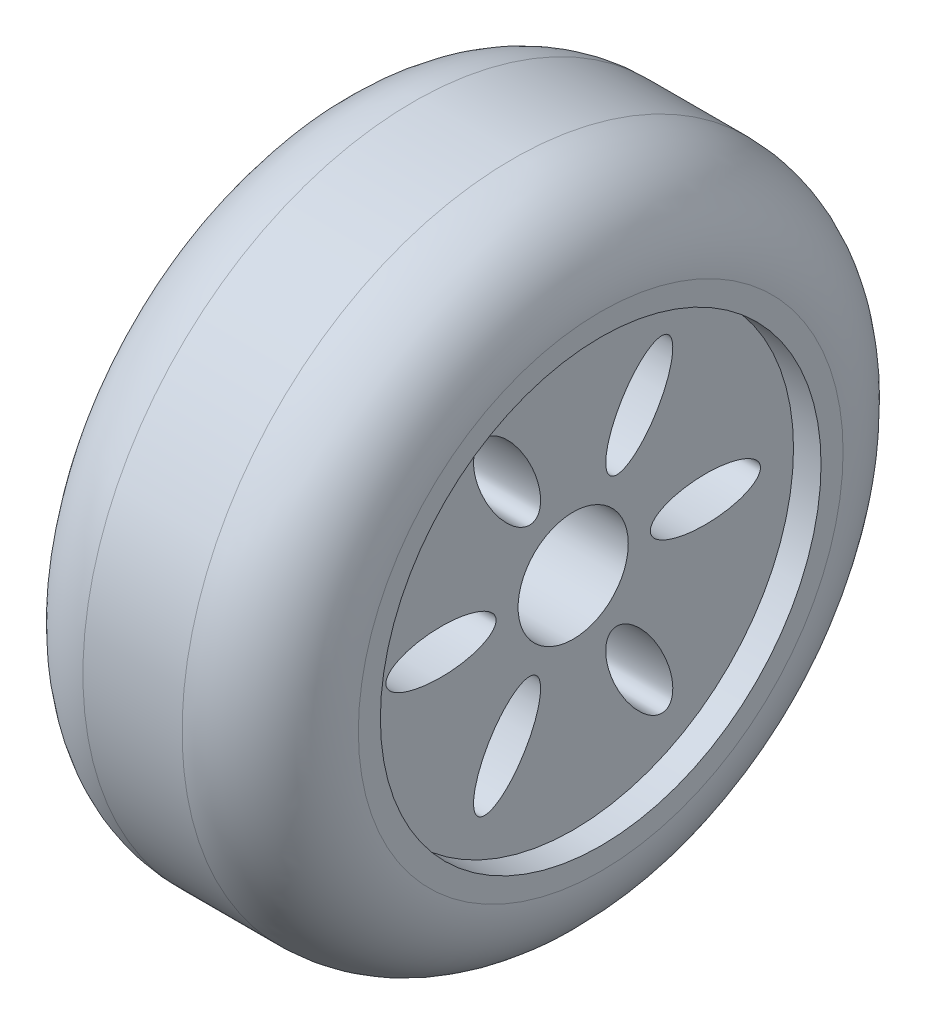
SolidWorks part; units mm, degrees
ref_plane "Front Plane" through (0, 0, 0) normal (0, 0, 1) x (1, 0, 0)
ref_plane "Top Plane" through (0, 0, 0) normal (0, 1, 0) x (1, 0, 0)
ref_plane "Right Plane" through (0, 0, 0) normal (1, 0, 0) x (0, 0, -1)
sketch "Sketch1" plane through (0, 0, 0) normal (1, 0, 0) x (0, 0, -1)
  circle A0 centre (0, 0) radius 30
  circle A1 centre (0, 0) radius 20
  dimension "D1" = 60
  dimension "D2" = 40
extrude "Boss-Extrude1" add sketch "Sketch1" along normal mid plane 25
fillet "Fillet1" radius 8 2 edges at (-12.5, 0, -30) (12.5, 0, -30)
sketch "Sketch2" plane through (0, 0, 0) normal (1, 0, 0) x (0, 0, -1)
  circle A0 centre (0, 0) radius 5
  circle A1 centre (0, 0) radius 20
  circle A17 centre (0, 0) radius 17
  ellipse E0 centre (-12, 0) end of major axis (-17, 0) minor radius 2
  ellipse E1 centre (-6, 10.3923) end of major axis (-8.5, 14.7224) minor radius 2
  ellipse E2 centre (6, 10.3923) end of major axis (8.5, 14.7224) minor radius 2
  ellipse E3 centre (12, 0) end of major axis (17, 0) minor radius 2
  ellipse E4 centre (6, -10.3923) end of major axis (8.5, -14.7224) minor radius 2
  ellipse E5 centre (-6, -10.3923) end of major axis (-8.5, -14.7224) minor radius 2
  point P43 (0, 0)
  dimension "D1" = 3
  dimension "D2" = 10
  dimension "D3" = 40
  dimension "D4" = 10
  dimension "D5" = 4
  dimension "D6" = 7
extrude "Boss-Extrude3" add sketch "Sketch2" along normal mid plane 20 separate body contours A1 A17 | A17 E5 E4 E3 E2 E1 E0 A0
